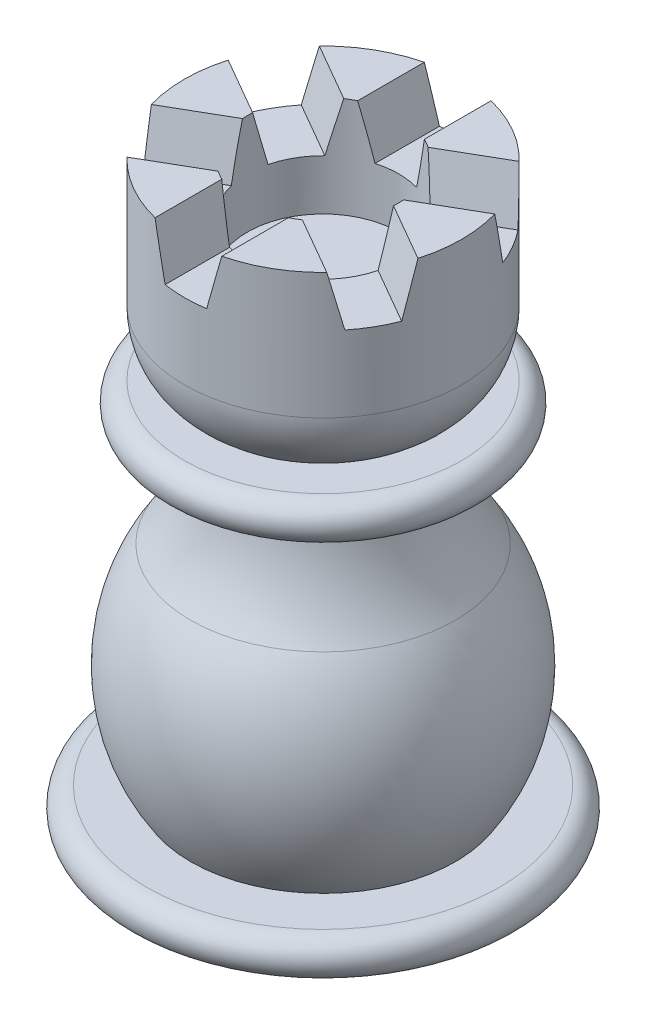
SolidWorks part; units mm, degrees
material "ABS"
ref_plane "Front Plane" through (0, 0, 0) normal (0, 0, 1) x (1, 0, 0)
ref_plane "Top Plane" through (0, 0, 0) normal (0, 1, 0) x (1, 0, 0)
ref_plane "Right Plane" through (0, 0, 0) normal (1, 0, 0) x (0, 0, -1)
sketch "Sketch1" plane through (0, 0, 0) normal (0, 0, 1) x (1, 0, 0)
  line L0 (0, 0) -> (11, 0)
  line L1 (11, 0) -> (11, -10)
  line L3 (8, -15.1962) -> (11, -15.1962)
  line L4 (11, -18.1962) -> (8, -18.1962)
  line L5 (10.5, -43) -> (14, -43)
  line L6 (14, -46) -> (0, -46)
  line L7 (0, 0) -> (0, -46) construction
  line L8 (0, 0) -> (0, -46)
  line L9 (13.0002, -34.7082) -> (13.0002, -43) construction
  arc A0 (11, -10) -> (8, -15.1962) centre (5, -10) cw
  arc A1 (11, -15.1962) -> (11, -18.1962) centre (11, -16.6962) cw
  arc A2 (8, -18.1962) -> (10.5, -26.4164) centre (22.9998, -18.1245) ccw
  arc A3 (10.5, -26.4164) -> (10.5, -43) centre (-1.9998, -34.7082) cw
  arc A4 (14, -43) -> (14, -46) centre (14, -44.5) cw
  dimension "D3" = 1.5
  dimension "D6" = 15
  dimension "D7" = 15
  dimension "D11" = 6
  dimension "D12" = 1.5
  dimension "D1" = 46
  dimension "D2" = 14
  dimension "D4" = 11
  dimension "D5" = 8
  dimension "D8" = 10
  dimension "D9" = 11
  dimension "D13" = 10.5
revolve "Revolve1" add sketch "Sketch1" angle 360 about L7
sketch "Sketch2" plane through (0, 0, 0) normal (0, 1, 0) x (1, 0, 0)
  circle A0 centre (0, 0) radius 6
  dimension "D1" = 12
extrude "Cut-Extrude1" cut sketch "Sketch2" against normal blind 8
sketch "Sketch3" plane through (0, 0, 0) normal (0, 0, 1) x (1, 0, 0)
  line L0 (-11, 0) -> (0, 0) construction
  line L1 (0, 0) -> (11, 0) construction
  line L2 (-2.646, 0) -> (-1.6487, -4)
  line L3 (-1.6487, -4) -> (1.6487, -4)
  line L4 (1.6487, -4) -> (2.354, 0)
  line L5 (-2.646, 0) -> (2.354, 0)
  line L6 (0, 0) -> (0, -16.4116) construction
  line L7 (6, 0) -> (-6, 0) construction
  line L9 (-2.646, 0) -> (2.354, 0) construction
  line L10 (11, 0) -> (-11, 0) construction
  point P1 (-11, 0)
  point P7 (-11, 0)
  point P13 (0, -4)
  point P14 (11, 0)
  point P17 (11, 0)
  point P20 (-2.646, 0)
  dimension "D1" = 24
  dimension "D2" = 5
  dimension "D3" = 4
  dimension "D4" = 10
extrude "Cut-Extrude2" cut sketch "Sketch3" against normal through all both and the other way through all
pattern_circular "CirPattern1" count 6 over 360 about axis through (0, 0, 0) along (0, 1, 0) of "Cut-Extrude2"
